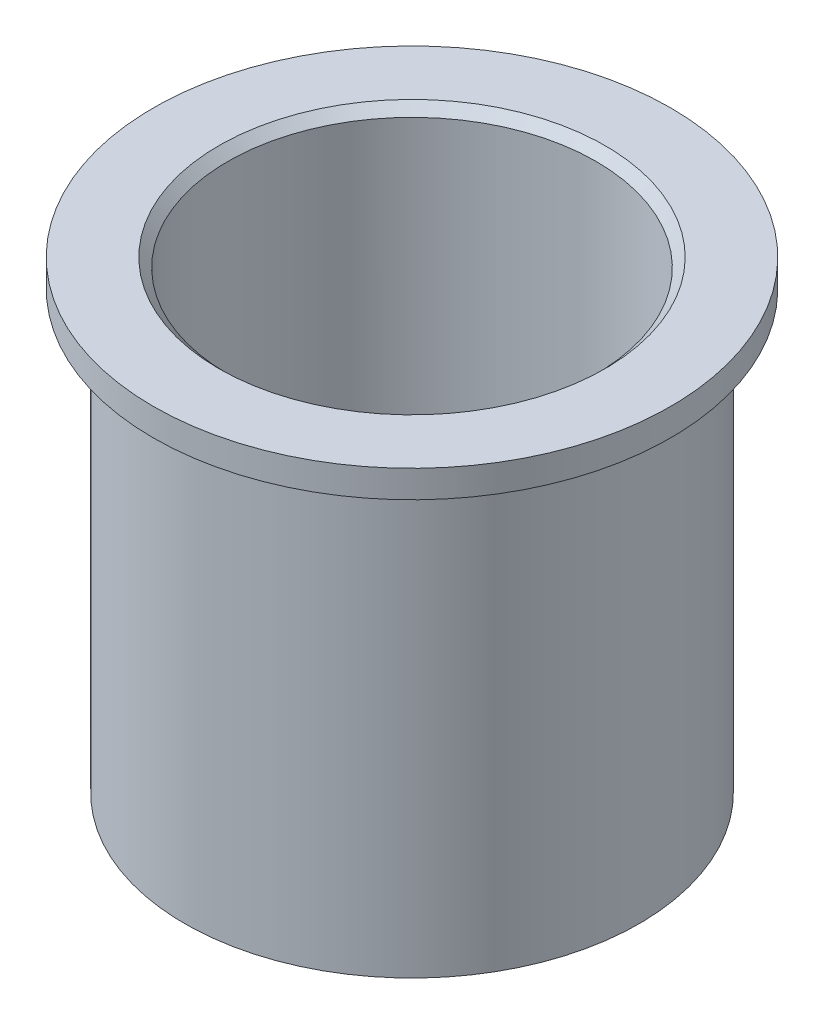
SolidWorks part; units mm, degrees
ref_plane "Front Plane" through (0, 0, 0) normal (0, 0, 1) x (1, 0, 0)
ref_plane "Top Plane" through (0, 0, 0) normal (0, 1, 0) x (1, 0, 0)
ref_plane "Right Plane" through (0, 0, 0) normal (1, 0, 0) x (0, 0, -1)
sketch "Sketch1" plane through (0, 0, 0) normal (0, 1, 0) x (1, 0, 0)
  circle A0 centre (0, 0) radius 12.7
  circle A1 centre (0, 0) radius 10.287
  dimension "D1" = 20.574
  dimension "D2" = 25.4
extrude "Boss-Extrude1" add sketch "Sketch1" along normal blind 24.384
sketch "Sketch2" plane through (0, 24.384, 0) normal (0, 1, 0) x (1, 0, 0)
  circle A0 centre (0, 0) radius 10.287
  circle A1 centre (0, 0) radius 14.4526
  circle A2 centre (0, 0) radius 12.7 construction
  dimension "D1" = 28.9052
  dimension "D2" = 20.574
extrude "Boss-Extrude2" add sketch "Sketch2" along normal blind 1.524
chamfer "Chamfer1" distance 0.508 angle 45 2 edges at (0, 0, 10.287) (0, 25.908, 10.287)
